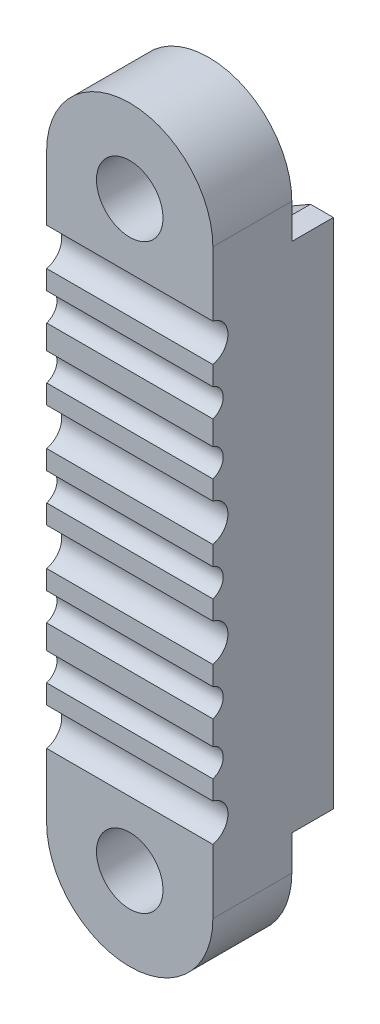
SolidWorks part; units mm, degrees
ref_plane "Спереди" through (0, 0, 0) normal (0, 0, 1) x (1, 0, 0)
ref_plane "Сверху" through (0, 0, 0) normal (0, 1, 0) x (1, 0, 0)
ref_plane "Справа" through (0, 0, 0) normal (1, 0, 0) x (0, 0, -1)
sketch "Эскиз1" plane through (0, 0, 0) normal (0, 0, 1) x (1, 0, 0)
  line L4 (0, 25.75) -> (0, -25.75)
  line L52 (-7.4224, -16) -> (-11.9484, -23.8394)
  line L53 (-11.9484, -23.8394) -> (-10.8453, -25.75)
  line L54 (-10.8453, -25.75) -> (0, -25.75)
  line L66 (0, 25.75) -> (-10.8453, 25.75)
  line L67 (-10.8453, 25.75) -> (-11.9484, 23.8394)
  line L68 (-11.9484, 23.8394) -> (-7.4224, 16)
  line L69 (-6.8865, 14) -> (-6.8865, -14)
  line L70 (-14.8865, -15.0184) -> (-14.8865, 15.0184)
  line L71 (-16.7525, 15.5184) -> (-20.2272, 9.5)
  line L72 (-26.2894, 6) -> (-35.4027, 6)
  line L73 (-35.4027, 6) -> (-35.4027, -6)
  line L74 (-35.4027, -6) -> (-26.2894, -6)
  line L75 (-20.2272, -9.5) -> (-16.7525, -15.5184)
  line L76 (0, -27.75) -> (0, -25.75)
  line L77 (0, -25.75) -> (-10.8453, -25.75)
  line L78 (-10.8453, -25.75) -> (-11.9484, -23.8394)
  line L79 (-11.9484, -23.8394) -> (-7.4224, -16)
  line L80 (-14.8865, -14) -> (-14.8865, -15.0184)
  line L81 (-16.7525, -15.5184) -> (-20.2272, -9.5)
  line L82 (-26.2894, -6) -> (-35.4027, -6)
  line L83 (-35.4027, -6) -> (-35.4027, -8)
  line L84 (-35.4027, -8) -> (-26.2894, -8)
  line L85 (-21.9593, -10.5) -> (-12, -27.75)
  line L86 (-12, -27.75) -> (0, -27.75)
  line L87 (-14.8865, -10.925) -> (-14.8865, -14)
  line L88 (-6.8865, -14) -> (-6.8865, -10.925)
  line L89 (-6.8865, -10.925) -> (-14.8865, -10.925)
  line L90 (-14.8865, 14) -> (-14.8865, 10.925)
  line L91 (-14.8865, 10.925) -> (-6.8865, 10.925)
  line L92 (-6.8865, 10.925) -> (-6.8865, 14)
  line L93 (-35.4027, 8) -> (-35.4027, 6)
  line L94 (-35.4027, 6) -> (-26.2894, 6)
  line L95 (-20.2272, 9.5) -> (-16.7525, 15.5184)
  line L96 (-14.8865, 15.0184) -> (-14.8865, 14)
  line L97 (-7.4224, 16) -> (-11.9484, 23.8394)
  line L98 (-11.9484, 23.8394) -> (-10.8453, 25.75)
  line L99 (-10.8453, 25.75) -> (0, 25.75)
  line L100 (0, 25.75) -> (0, 27.75)
  line L101 (0, 27.75) -> (-12, 27.75)
  line L102 (-12, 27.75) -> (-21.9593, 10.5)
  line L103 (-26.2894, 8) -> (-35.4027, 8)
  arc A16 (-6.8865, 14) -> (-7.4224, 16) centre (-10.8865, 14) ccw
  arc A17 (-7.4224, -16) -> (-6.8865, -14) centre (-10.8865, -14) ccw
  arc A18 (-16.7525, -15.5184) -> (-14.8865, -15.0184) centre (-15.8865, -15.0184) ccw
  arc A19 (-14.8865, 15.0184) -> (-16.7525, 15.5184) centre (-15.8865, 15.0184) ccw
  arc A20 (-26.2894, 6) -> (-20.2272, 9.5) centre (-26.2894, 13) ccw
  arc A21 (-20.2272, -9.5) -> (-26.2894, -6) centre (-26.2894, -13) ccw
  arc A22 (-14.8865, -14) -> (-7.4224, -16) centre (-10.8865, -14) ccw
  arc A23 (-16.7525, -15.5184) -> (-14.8865, -15.0184) centre (-15.8865, -15.0184) ccw
  arc A24 (-20.2272, -9.5) -> (-26.2894, -6) centre (-26.2894, -13) ccw
  arc A25 (-21.9593, -10.5) -> (-26.2894, -8) centre (-26.2894, -13) ccw
  arc A26 (-14.8865, -14) -> (-6.8865, -14) centre (-10.8865, -14) ccw
  arc A27 (-6.8865, 14) -> (-14.8865, 14) centre (-10.8865, 14) ccw
  arc A28 (-26.2894, 6) -> (-20.2272, 9.5) centre (-26.2894, 13) ccw
  arc A29 (-14.8865, 15.0184) -> (-16.7525, 15.5184) centre (-15.8865, 15.0184) ccw
  arc A30 (-7.4224, 16) -> (-14.8865, 14) centre (-10.8865, 14) ccw
  arc A31 (-26.2894, 8) -> (-21.9593, 10.5) centre (-26.2894, 13) ccw
  circle A34 centre (-10.8865, -14) radius 1.6
  circle A35 centre (-10.8865, 14) radius 1.6
sketch "Эскиз2" plane through (0, 0, 0) normal (0, 0, 1) x (1, 0, 0)
  line L0 (-14.8865, 14) -> (-14.8865, -14)
  line L1 (-6.8865, 14) -> (-6.8865, -14)
  arc A0 (-14.8865, -14) -> (-6.8865, -14) centre (-10.8865, -14) ccw
  arc A1 (-6.8865, 14) -> (-14.8865, 14) centre (-10.8865, 14) ccw
  circle A2 centre (-10.8865, -14) radius 1.6 construction
  circle A3 centre (-10.8865, 14) radius 1.6 construction
  circle A4 centre (-10.8865, -14) radius 1.6
  circle A5 centre (-10.8865, 14) radius 1.6
extrude "Бобышка-Вытянуть1" add sketch "Эскиз2" along normal blind 3.8
sketch "Эскиз3" plane through (-14.8865, 0, 0) normal (-1, 0, 0) x (0, 0, 1)
  line L16 (4, 9.075) -> (4, 8.2) construction
  line L17 (4, 6.8) -> (4, 5.7) construction
  line L18 (4, 4.3) -> (4, 3.425) construction
  line L19 (4, 1.575) -> (4, 0.7) construction
  line L20 (4, -0.7) -> (4, -1.575) construction
  line L21 (4, -3.425) -> (4, -4.3) construction
  line L22 (4, -5.7) -> (4, -6.8) construction
  line L23 (4, -8.2) -> (4, -9.075) construction
  circle A0 centre (4, -10) radius 0.925
  circle A1 centre (4, -7.5) radius 0.7
  circle A2 centre (4, -5) radius 0.7
  circle A3 centre (4, 10) radius 0.925
  circle A4 centre (4, 7.5) radius 0.7
  circle A5 centre (4, 5) radius 0.7
  circle A6 centre (4, 2.5) radius 0.925
  circle A7 centre (4, 0) radius 0.7
  circle A8 centre (4, -2.5) radius 0.925
extrude "Вырез-Вытянуть1" cut sketch "Эскиз3" against normal up to next
sketch "Эскиз4" plane through (0, 0, 0) normal (0, 0, -1) x (-1, 0, 0)
  line L0 (0, 0) -> (14.8865, 0) construction
  line L1 (10.8865, 10.6514) -> (13.7865, 12.3257)
  line L2 (13.7865, 12.3257) -> (13.7865, 15.6743) construction
  line L3 (13.7865, 15.6743) -> (10.8865, 17.3486) construction
  line L4 (10.8865, 17.3486) -> (7.9865, 15.6743) construction
  line L5 (7.9865, 15.6743) -> (7.9865, 12.3257) construction
  line L6 (7.9865, 12.3257) -> (10.8865, 10.6514)
  line L7 (14.8865, 14) -> (14.8865, -14) construction
  line L8 (7.9865, 12.3257) -> (6.8865, 12.3257)
  line L9 (6.8865, -14) -> (6.8865, 14) construction
  line L10 (6.8865, 12.3257) -> (6.8865, -12.3257)
  line L11 (13.7865, 12.3257) -> (14.8865, 12.3257)
  line L12 (14.8865, 12.3257) -> (14.8865, -12.3257)
  line L13 (13.7865, -12.3257) -> (14.8865, -12.3257)
  line L14 (7.9865, -12.3257) -> (6.8865, -12.3257)
  line L15 (7.9865, -12.3257) -> (10.8865, -10.6514)
  line L16 (10.8865, -10.6514) -> (13.7865, -12.3257)
  circle A0 centre (10.8865, 14) radius 2.9 construction
  point P22 (6.8865, 0)
  dimension "D1" = 5.8
extrude "Бобышка-Вытянуть2" add sketch "Эскиз4" along normal blind 2
